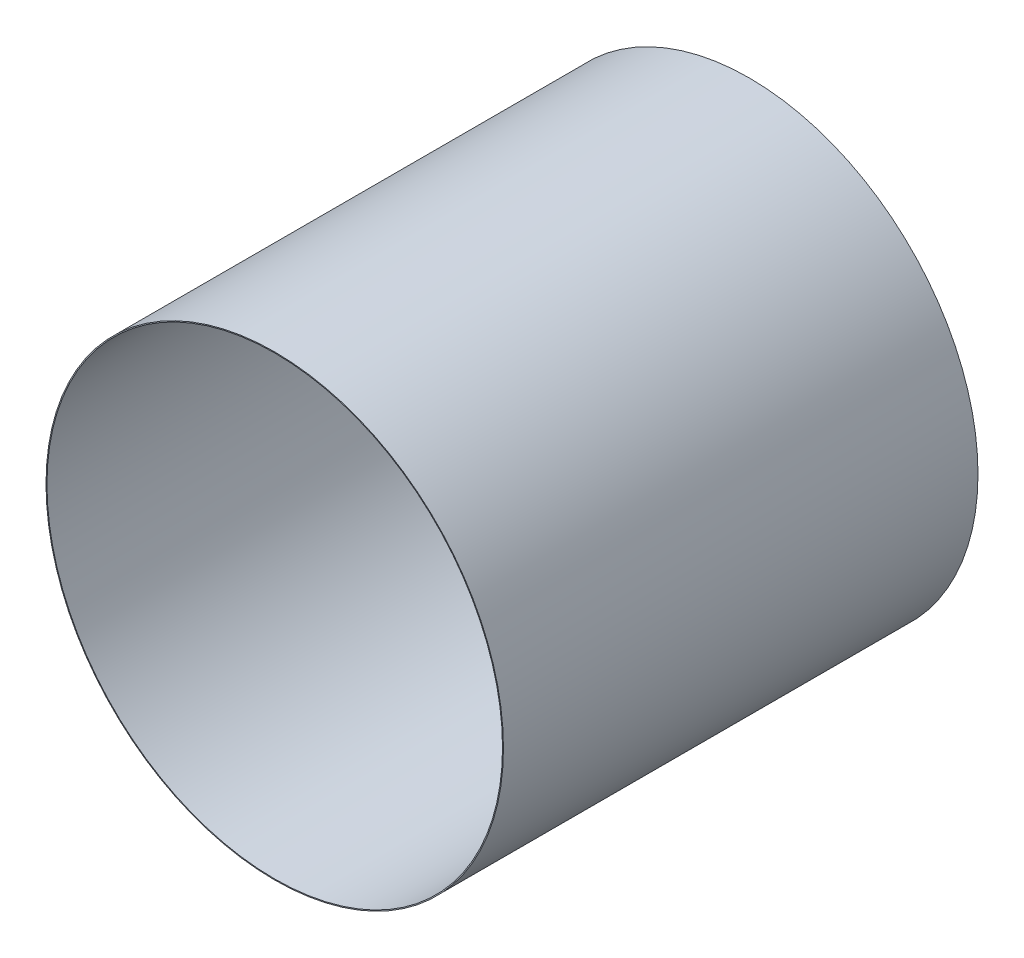
SolidWorks part; units mm, degrees
ref_plane "Front Plane" through (0, 0, 0) normal (0, 0, 1) x (1, 0, 0)
ref_plane "Top Plane" through (0, 0, 0) normal (0, 1, 0) x (1, 0, 0)
ref_plane "Right Plane" through (0, 0, 0) normal (1, 0, 0) x (0, 0, -1)
sketch "Sketch1" plane through (0, 0, 0) normal (0, 0, 1) x (1, 0, 0)
  circle A0 centre (0, 0) radius 12.05
  circle A1 centre (0, 0) radius 12
  dimension "D1" = 24
  dimension "D2" = 24.1
extrude "Boss-Extrude1" add sketch "Sketch1" along normal blind 25
